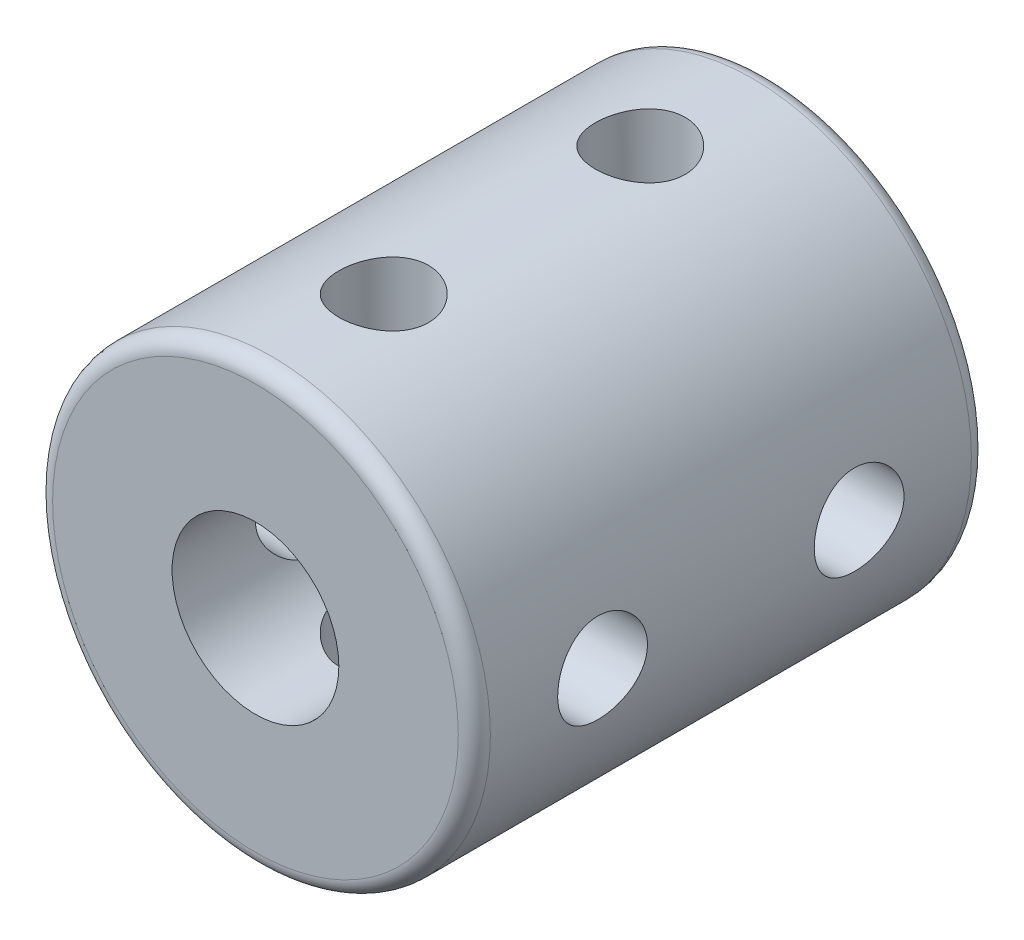
SolidWorks part; units mm, degrees
ref_plane "Front Plane" through (0, 0, 0) normal (0, 0, 1) x (1, 0, 0)
ref_plane "Top Plane" through (0, 0, 0) normal (0, 1, 0) x (1, 0, 0)
ref_plane "Right Plane" through (0, 0, 0) normal (1, 0, 0) x (0, 0, -1)
sketch "Sketch1" plane through (0, 0, 0) normal (0, 0, 1) x (1, 0, 0)
  circle A0 centre (0, 0) radius 2.6
  circle A1 centre (0, 0) radius 6.825
  dimension "D1" = 5.2
  dimension "D2" = 13.65
extrude "Boss-Extrude1" add sketch "Sketch1" along normal blind 16
sketch "Sketch3" plane through (0, 0, 0) normal (0, 1, 0) x (1, 0, 0)
  line L0 (-6.825, -16) -> (6.825, -16) construction
  circle A0 centre (0, -12) radius 1.4
  dimension "D1" = 2.8
  dimension "D2" = 4
extrude "Cut-Extrude2" cut sketch "Sketch3" against normal blind 10
pattern_circular "CirPattern1" count 4 over 360 about axis through (0, 0, 16) along (0, 0, -1) of "Cut-Extrude2"
fillet "Fillet1" radius 0.5 3 edges at (2.6, 0, 0) (6.825, 0, 0) (6.825, 0, 16)
ref_plane "Plane1" through (0, 0, 8) normal (0, 0, 1) x (1, 0, 0)
mirror "Mirror1" about plane through (0, 0, 8) normal (0, 0, 1) of "Cut-Extrude2", "CirPattern1"
